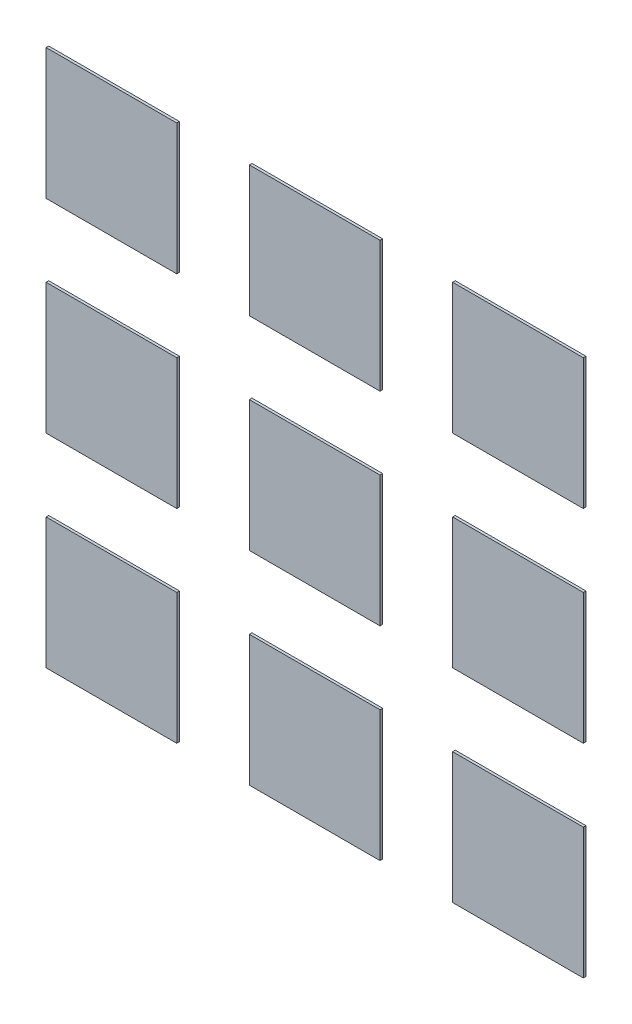
SolidWorks part; units mm, degrees
ref_plane "Přední rovina" through (0, 0, 0) normal (0, 0, 1) x (1, 0, 0)
ref_plane "Horní rovina" through (0, 0, 0) normal (0, 1, 0) x (1, 0, 0)
ref_plane "Pravá rovina" through (0, 0, 0) normal (1, 0, 0) x (0, 0, -1)
sketch "Skica1" plane through (0, 0, 0) normal (0, 0, 1) x (1, 0, 0)
  line L0 (-0.95, 1.85) -> (-0.95, 0.95)
  line L5 (1.85, -1.85) -> (0.95, -1.85)
  line L6 (1.85, -1.85) -> (1.85, -0.95)
  line L7 (1.85, 1.85) -> (0.95, 1.85)
  line L8 (-1.85, -1.85) -> (-1.85, -0.95)
  line L25 (-0.45, 1.85) -> (-0.45, 0.95)
  line L26 (0.45, 1.85) -> (0.45, 0.95)
  line L27 (0.95, -1.85) -> (0.95, -0.95)
  line L28 (1.85, 0.95) -> (0.95, 0.95)
  line L29 (-1.85, 0.45) -> (-0.95, 0.45)
  line L30 (1.85, -0.45) -> (0.95, -0.45)
  line L31 (-1.85, -0.95) -> (-0.95, -0.95)
  line L32 (-1.85, 0.95) -> (-1.85, 1.85)
  line L33 (-0.95, 0.45) -> (-0.95, -0.45)
  line L34 (-0.45, 0.45) -> (-0.45, -0.45)
  line L35 (0.45, 0.45) -> (0.45, -0.45)
  line L36 (0.95, 0.95) -> (0.95, 1.85)
  line L37 (1.85, 0.95) -> (1.85, 1.85)
  line L38 (1.85, -0.45) -> (1.85, 0.45)
  line L39 (0.95, -0.45) -> (0.95, 0.45)
  line L40 (0.45, -0.95) -> (0.45, -1.85)
  line L41 (-0.45, -0.95) -> (-0.45, -1.85)
  line L42 (-0.95, -0.95) -> (-0.95, -1.85)
  line L43 (-1.85, -0.45) -> (-1.85, 0.45)
  line L44 (-1.85, 0.95) -> (-1.85, 0.45) construction
  line L45 (-0.95, 0.95) -> (-0.95, 0.45) construction
  line L46 (-0.45, 0.95) -> (-0.45, 0.45) construction
  line L47 (0.45, 0.95) -> (0.45, 0.45) construction
  line L48 (0.95, 0.95) -> (0.95, 0.45) construction
  line L49 (1.85, 0.95) -> (1.85, 0.45) construction
  line L50 (-1.85, -0.45) -> (-1.85, -0.95) construction
  line L51 (-0.95, -0.45) -> (-0.95, -0.95) construction
  line L52 (0.45, -0.45) -> (0.45, -0.95) construction
  line L53 (-0.45, -0.45) -> (-0.45, -0.95) construction
  line L54 (1.85, -0.45) -> (1.85, -0.95) construction
  line L55 (0.95, -0.45) -> (0.95, -0.95) construction
  line L56 (-0.95, 1.85) -> (-1.85, 1.85)
  line L57 (-0.95, 0.95) -> (-1.85, 0.95)
  line L58 (-0.45, 0.45) -> (0.45, 0.45)
  line L59 (-0.95, -0.45) -> (-1.85, -0.45)
  line L60 (-0.45, -0.95) -> (0.45, -0.95)
  line L61 (-0.95, -1.85) -> (-1.85, -1.85)
  line L62 (0.45, -1.85) -> (-0.45, -1.85)
  line L63 (0.95, -0.95) -> (1.85, -0.95)
  line L64 (0.45, -0.45) -> (-0.45, -0.45)
  line L65 (0.95, 0.45) -> (1.85, 0.45)
  line L66 (0.45, 0.95) -> (-0.45, 0.95)
  line L67 (0.45, 1.85) -> (-0.45, 1.85)
  line L68 (-0.95, 1.85) -> (-0.45, 1.85) construction
  line L69 (0.45, 0.95) -> (0.95, 0.95) construction
  line L70 (0.95, 0.45) -> (0.45, 0.45) construction
  line L71 (-0.45, 0.45) -> (-0.95, 0.45) construction
  line L72 (-0.95, 0.95) -> (-0.45, 0.95) construction
  line L73 (0.45, 1.85) -> (0.95, 1.85) construction
  line L74 (0.95, -0.45) -> (0.45, -0.45) construction
  line L75 (0.45, -0.95) -> (0.95, -0.95) construction
  line L76 (0.95, -1.85) -> (0.45, -1.85) construction
  line L77 (-0.45, -1.85) -> (-0.95, -1.85) construction
  line L78 (-0.95, -0.95) -> (-0.45, -0.95) construction
  line L79 (-0.45, -0.45) -> (-0.95, -0.45) construction
  line L80 (-0.45, -0.45) -> (0.45, 0.45) construction
  point P0 (0, 0)
  dimension "D1" = 0.9
  dimension "D2" = 0.5
  dimension "D3" = 3.7
extrude "Přidat vysunutím1" add sketch "Skica1" along normal blind 0.018
equation "\"thickness\"=0.018"
equation "\"D1@Přidat vysunutím1\"=\"thickness\""
